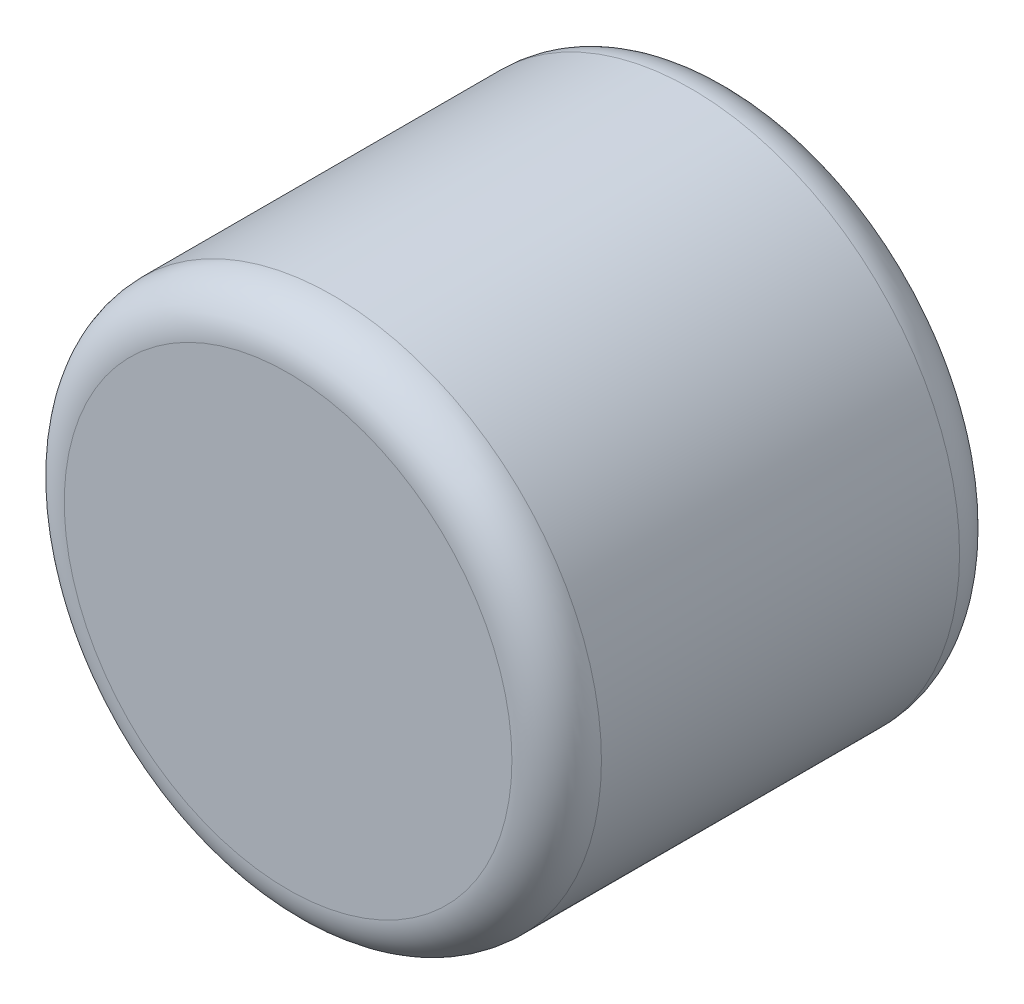
SolidWorks part; units mm, degrees
ref_plane "Front Plane" through (0, 0, 0) normal (0, 0, 1) x (1, 0, 0)
ref_plane "Top Plane" through (0, 0, 0) normal (0, 1, 0) x (1, 0, 0)
ref_plane "Right Plane" through (0, 0, 0) normal (1, 0, 0) x (0, 0, -1)
sketch "Sketch1" plane through (0, 0, 0) normal (0, 0, 1) x (1, 0, 0)
  circle A0 centre (0, 0) radius 30
  dimension "D1" = 60
extrude "Boss-Extrude1" add sketch "Sketch1" along normal mid plane 50
fillet "Fillet1" radius 5 2 edges at (30, 0, -25) (30, 0, 25)
